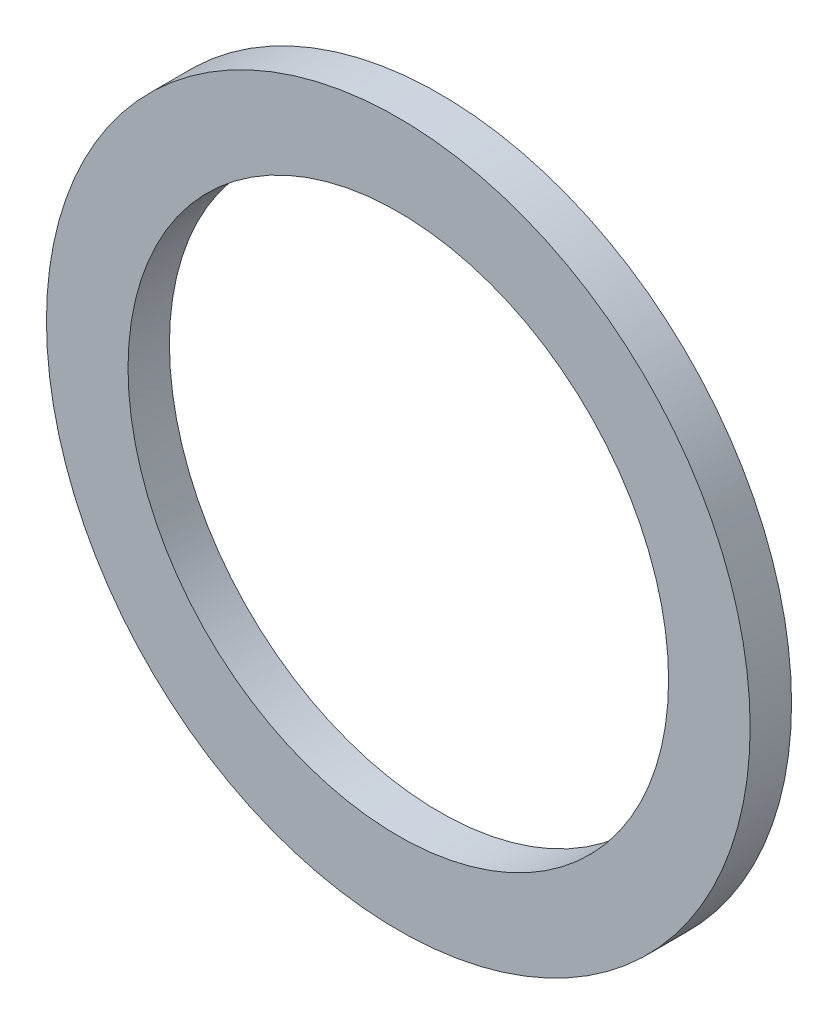
SolidWorks part; units mm, degrees
material "Copper"
ref_plane "Front Plane" through (0, 0, 0) normal (0, 0, 1) x (1, 0, 0)
ref_plane "Top Plane" through (0, 0, 0) normal (0, 1, 0) x (1, 0, 0)
ref_plane "Right Plane" through (0, 0, 0) normal (1, 0, 0) x (0, 0, -1)
sketch "Sketch1" plane through (0, 0, 0) normal (0, 0, 1) x (1, 0, 0)
  circle A0 centre (0, 0) radius 11.1
  circle A1 centre (0, 0) radius 14.45
  dimension "ID" = 22.2
  dimension "OD" = 28.9
extrude "Extrude1" add sketch "Sketch1" against normal blind 1.7
